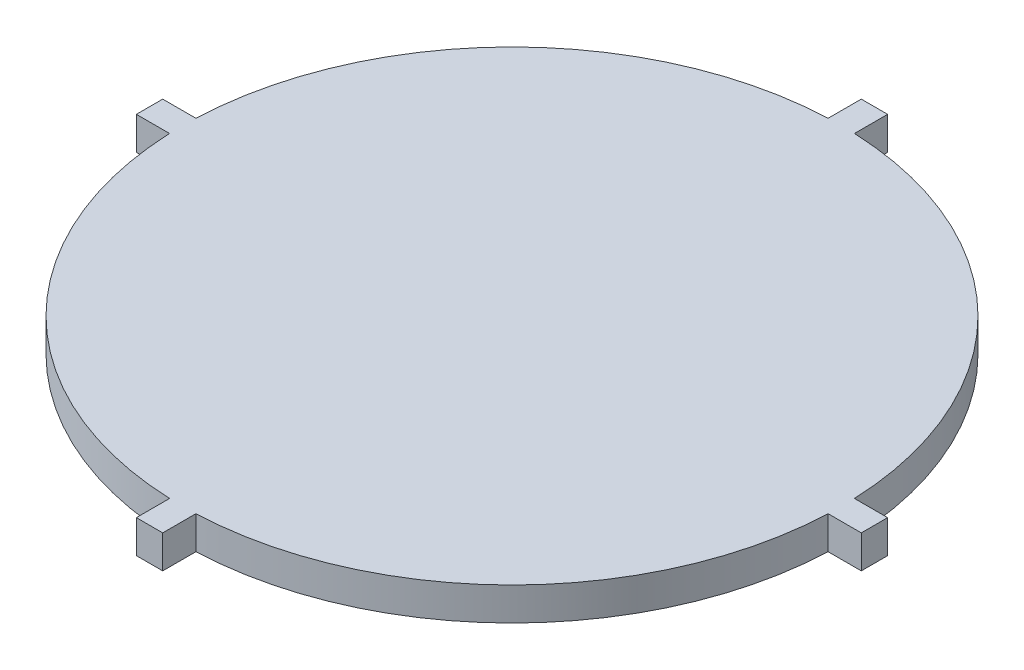
SolidWorks part; units mm, degrees
ref_plane "前视基准面" through (0, 0, 0) normal (0, 0, 1) x (1, 0, 0)
ref_plane "上视基准面" through (0, 0, 0) normal (0, 1, 0) x (1, 0, 0)
ref_plane "右视基准面" through (0, 0, 0) normal (1, 0, 0) x (0, 0, -1)
sketch "草图3" plane through (0, 0, 0) normal (0, 1, 0) x (1, 0, 0)
  line L2 (0, 110) -> (-4, 110)
  line L3 (-4, 110) -> (-4, 99.92)
  line L4 (0, 110) -> (4, 110)
  line L5 (4, 110) -> (4, 99.92)
  line L6 (0, 110) -> (-4, 109) construction
  line L7 (0, 110) -> (4, 109) construction
  line L8 (110, -4) -> (99.92, -4)
  line L9 (110, 0) -> (110, 4)
  line L10 (110, 4) -> (99.92, 4)
  line L11 (-4, -110) -> (-4, -99.92)
  line L12 (0, -110) -> (4, -110)
  line L13 (4, -110) -> (4, -99.92)
  line L14 (-110, 4) -> (-99.92, 4)
  line L15 (-110, 0) -> (-110, -4)
  line L16 (-110, -4) -> (-99.92, -4)
  line L17 (-110, 0) -> (-110, 4)
  line L18 (-4, -110) -> (0, -110)
  line L19 (110, 0) -> (110, -4)
  arc A0 (-4, 99.92) -> (-99.92, 4) centre (0, 0) ccw
  arc A1 (-99.92, -4) -> (-4, -99.92) centre (0, 0) ccw
  arc A2 (4, -99.92) -> (99.92, -4) centre (0, 0) ccw
  arc A3 (99.92, 4) -> (4, 99.92) centre (0, 0) ccw
  dimension "D1" = 4
extrude "凸台-拉伸2" add sketch "草图3" along normal blind 10
